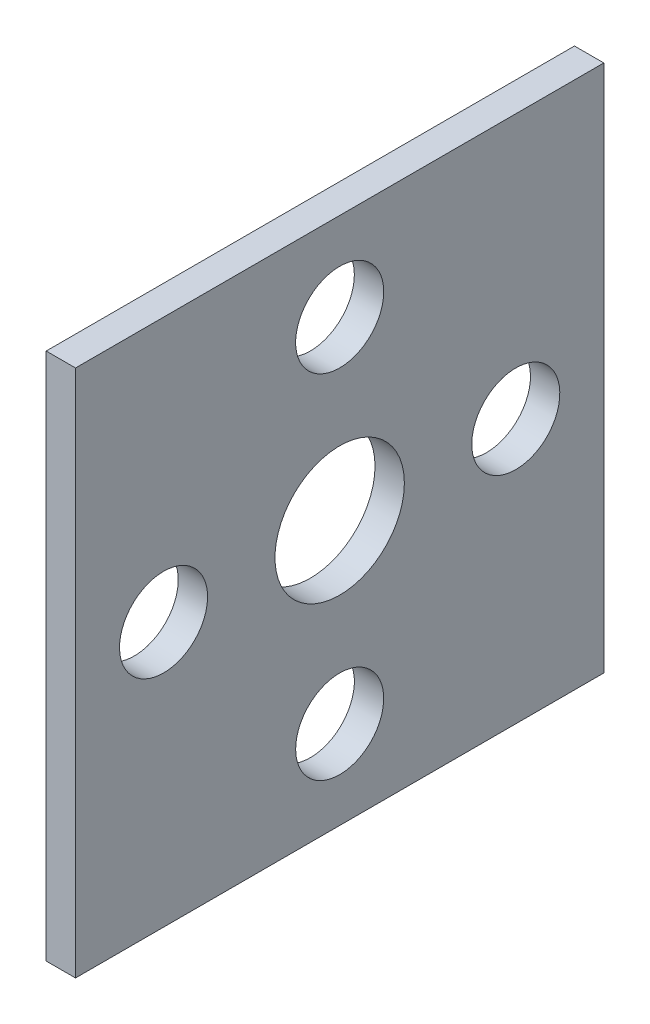
SolidWorks part; units mm, degrees
material "1023 Carbon Steel Sheet (SS)"
ref_plane "Front Plane" through (0, 0, 0) normal (0, 0, 1) x (1, 0, 0)
ref_plane "Top Plane" through (0, 0, 0) normal (0, 1, 0) x (1, 0, 0)
ref_plane "Right Plane" through (0, 0, 0) normal (1, 0, 0) x (0, 0, -1)
sketch "Sketch1" plane through (0, 0, 0) normal (1, 0, 0) x (0, 0, -1)
  line L1 (-28.575, -28.575) -> (28.575, -28.575)
  line L2 (-28.575, -28.575) -> (-28.575, 28.575)
  line L3 (-28.575, 28.575) -> (28.575, 28.575)
  line L4 (28.575, -28.575) -> (28.575, 28.575)
  line L5 (-28.575, -28.575) -> (28.575, 28.575) construction
  line L6 (-28.575, 28.575) -> (28.575, -28.575) construction
  circle A1 centre (0, 0) radius 6.999
  circle A2 centre (0, 0) radius 11.1125 construction
  dimension "D1" = 13.9979
  dimension "D2" = 22.225
  dimension "D3" = 57.15
  dimension "D4" = 57.15
extrude "Boss-Extrude1" add sketch "Sketch1" along normal blind 3.175
sketch "Sketch2" plane through (0, 0, 0) normal (1, 0, 0) x (0, 0, -1)
  line L0 (-28.575, 0) -> (28.575, 0) construction
  line L1 (28.575, -28.575) -> (28.575, 28.575) construction
  line L2 (0, -28.575) -> (0, 28.575) construction
  line L3 (28.575, 28.575) -> (-28.575, 28.575) construction
  circle A0 centre (0, 19.05) radius 4.7625
  point P7 (0, 0)
  point P12 (0, 0)
  point P16 (0, 0)
  dimension "D2" = 9.525
  dimension "D1" = 19.05
extrude "Cut-Extrude1" cut sketch "Sketch2" along normal through all
pattern_circular "CirPattern1" count 4 over 360 about axis through (0, 0, 0) along (1, 0, 0) of "Cut-Extrude1"
